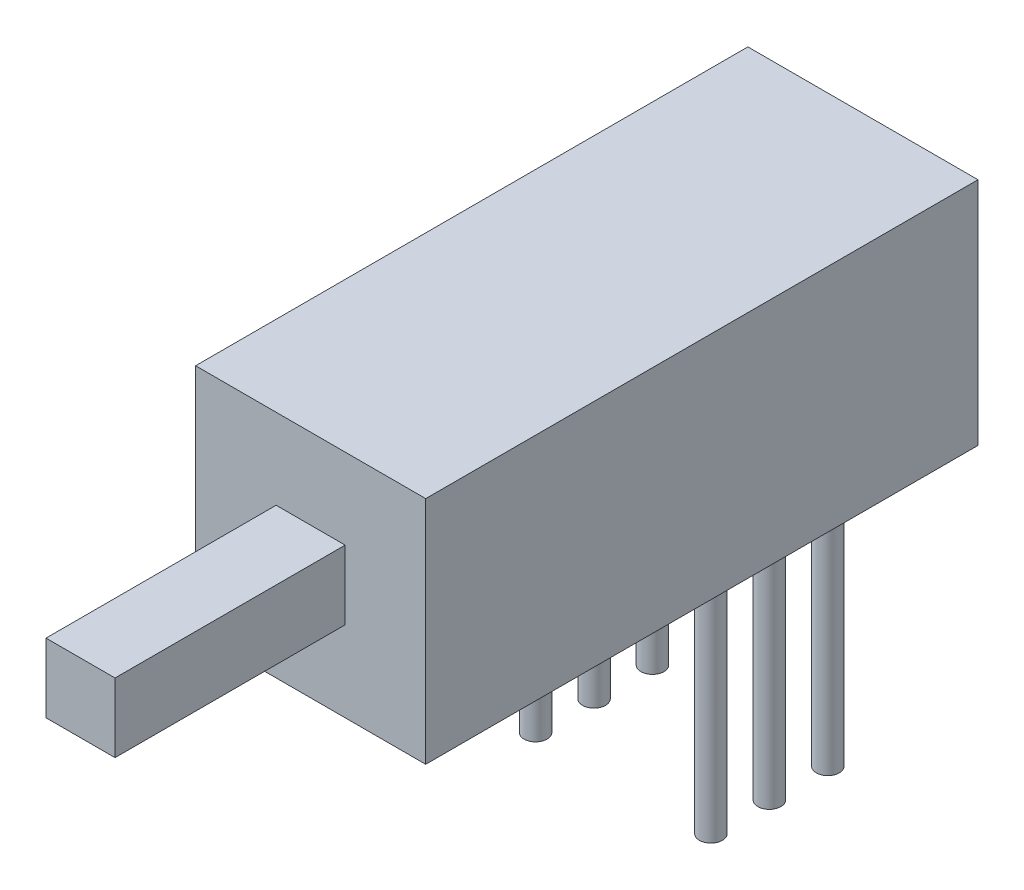
SolidWorks part; units mm, degrees
ref_plane "Front Plane" through (0, 0, 0) normal (0, 0, 1) x (1, 0, 0)
ref_plane "Top Plane" through (0, 0, 0) normal (0, 1, 0) x (1, 0, 0)
ref_plane "Right Plane" through (0, 0, 0) normal (1, 0, 0) x (0, 0, -1)
sketch "Sketch1" plane through (0, 0, 0) normal (0, 0, 1) x (1, 0, 0)
  line L1 (-5, -5) -> (5, -5)
  line L2 (-5, -5) -> (-5, 5)
  line L3 (-5, 5) -> (5, 5)
  line L4 (5, -5) -> (5, 5)
  line L5 (-5, -5) -> (5, 5) construction
  line L6 (-5, 5) -> (5, -5) construction
  point P0 (0, 0)
  dimension "D1" = 10
  dimension "D2" = 10
extrude "Boss-Extrude1" add sketch "Sketch1" along normal blind 24 contours L3 L4 L1 L2
sketch "Sketch2" plane through (0, 0, 24) normal (0, 0, 1) x (1, 0, 0)
  line L1 (-1.5, -1.5) -> (1.5, -1.5)
  line L2 (-1.5, -1.5) -> (-1.5, 1.5)
  line L3 (-1.5, 1.5) -> (1.5, 1.5)
  line L4 (1.5, -1.5) -> (1.5, 1.5)
  line L5 (-1.5, -1.5) -> (1.5, 1.5) construction
  line L6 (-1.5, 1.5) -> (1.5, -1.5) construction
  point P0 (0, 0)
  dimension "D1" = 3
  dimension "D2" = 3
extrude "Boss-Extrude2" add sketch "Sketch2" along normal blind 10 contours L3 L4 L1 L2
sketch "Sketch3" plane through (0, -5, 0) normal (0, -1, 0) x (1, 0, 0)
  line L0 (-3.81, 10.4156) -> (3.81, 10.4156) construction
  line L1 (-3.81, 7.8756) -> (-3.81, 10.4156) construction
  line L3 (0, 0) -> (0, 10.4156) construction
  line L4 (-5, 0) -> (5, 0) construction
  circle A0 centre (-3.81, 10.4156) radius 0.5
  circle A1 centre (3.81, 10.4156) radius 0.5
  circle A2 centre (3.81, 7.8756) radius 0.5
  circle A3 centre (3.81, 5.3356) radius 0.5
  circle A4 centre (-3.81, 7.8756) radius 0.5
  circle A5 centre (-3.81, 5.3356) radius 0.5
  point P16 (3.81, 5.3356)
  dimension "D3" = 1
  dimension "D4" = 2.54
  dimension "D5" = 7.62
  dimension "D1" = 2
  dimension "D2" = 3
extrude "Boss-Extrude3" add sketch "Sketch3" along normal blind 10
